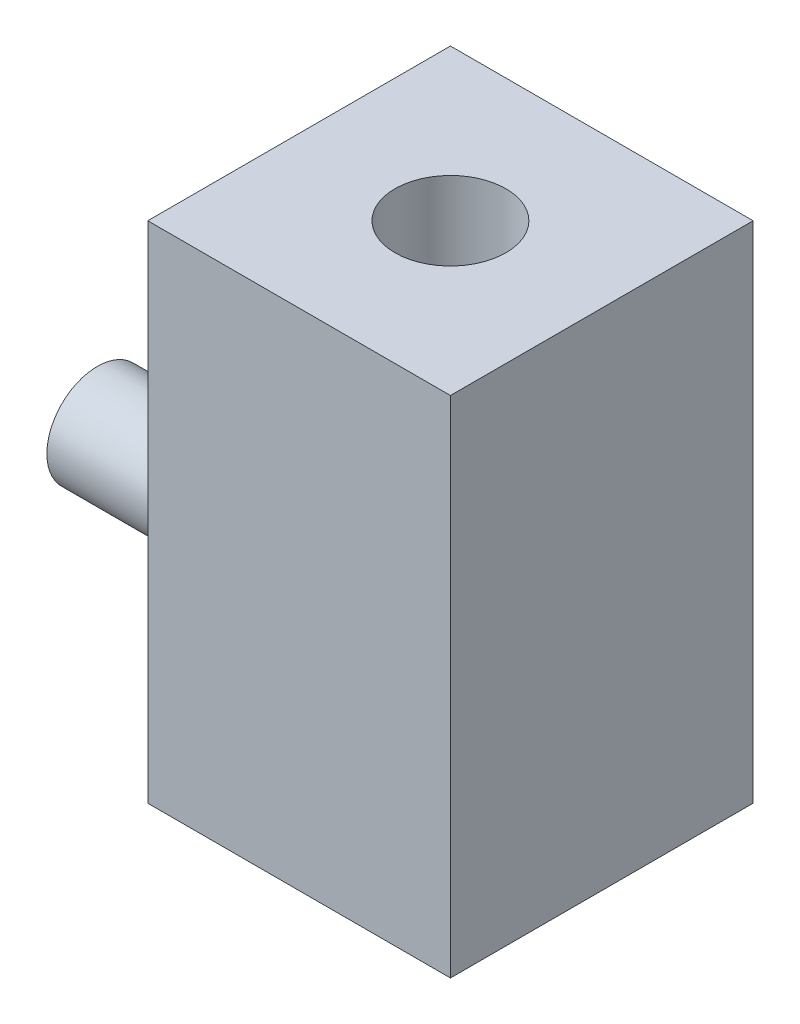
SolidWorks part; units mm, degrees
ref_plane "Front Plane" through (0, 0, 0) normal (0, 0, 1) x (1, 0, 0)
ref_plane "Top Plane" through (0, 0, 0) normal (0, 1, 0) x (1, 0, 0)
ref_plane "Right Plane" through (0, 0, 0) normal (1, 0, 0) x (0, 0, -1)
sketch "Sketch1" plane through (0, 0, 0) normal (0, 0, 1) x (1, 0, 0)
  line L1 (-38.1, 63.5) -> (38.1, 63.5)
  line L2 (-38.1, 63.5) -> (-38.1, -63.5)
  line L3 (-38.1, -63.5) -> (38.1, -63.5)
  line L4 (38.1, 63.5) -> (38.1, -63.5)
  line L5 (-38.1, 63.5) -> (38.1, -63.5) construction
  line L6 (-38.1, -63.5) -> (38.1, 63.5) construction
  point P0 (0, 0)
extrude "Boss-Extrude1" add sketch "Sketch1" along normal blind 76.2
sketch "Sketch2" plane through (0, 63.5, 0) normal (0, 1, 0) x (1, 0, 0)
  line L0 (38.1, -76.2) -> (-38.1, 0) construction
  line L1 (-55, 0) -> (55, 0) construction
  line L2 (-38.1, -76.2) -> (-38.1, 0) construction
  line L3 (38.1, 0) -> (-38.1, -76.2) construction
  line L4 (38.1, -76.2) -> (38.1, 0) construction
  circle A0 centre (0, -38.1) radius 13.97
  dimension "D1" = 27.94
extrude "Cut-Extrude1" cut sketch "Sketch2" against normal blind 48.26
sketch "Sketch3" plane through (-38.1, 0, 0) normal (-1, 0, 0) x (0, 0, 1)
  line L0 (76.2, 63.5) -> (76.2, -63.5) construction
  line L1 (76.2, -63.5) -> (0, -63.5) construction
  circle A0 centre (38.1, -25.4) radius 12.7
  dimension "D1" = 25.4
  dimension "D3" = 38.1
  dimension "D2" = 38.1
extrude "Boss-Extrude2" add sketch "Sketch3" along normal blind 50.8
